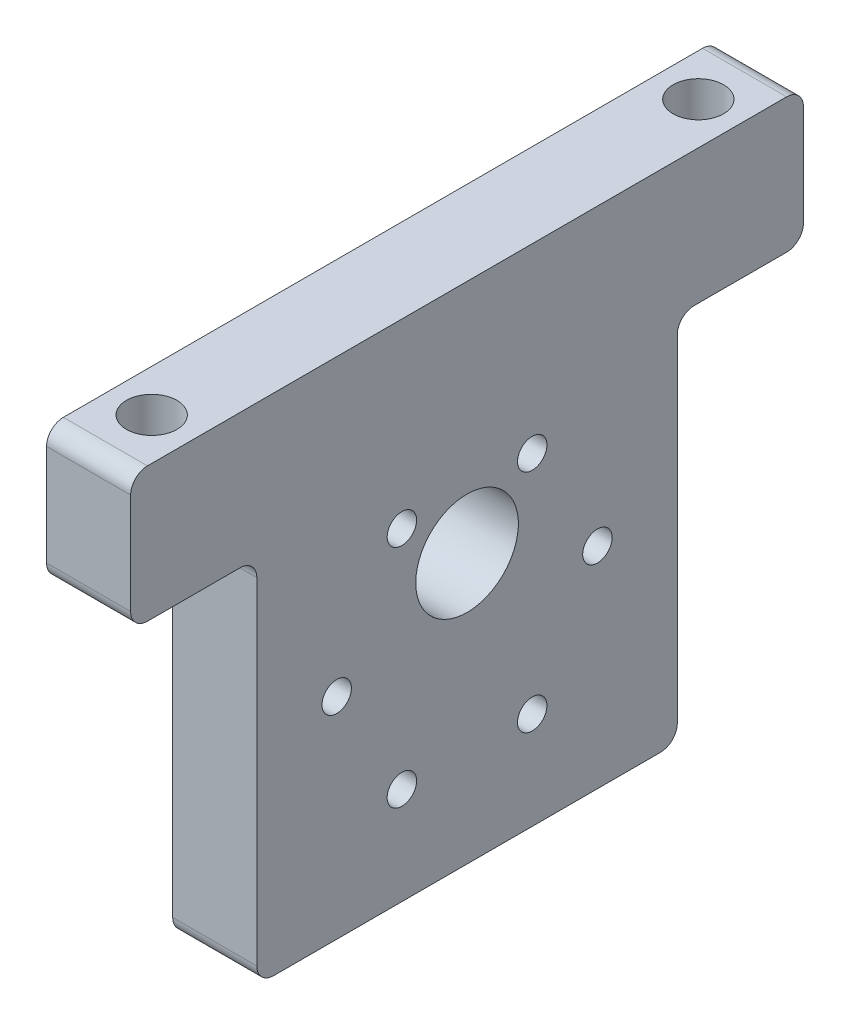
SolidWorks part; units mm, degrees
material "Alloy Steel"
ref_plane "Front Plane" through (0, 0, 0) normal (0, 0, 1) x (1, 0, 0)
ref_plane "Top Plane" through (0, 0, 0) normal (0, 1, 0) x (1, 0, 0)
ref_plane "Right Plane" through (0, 0, 0) normal (1, 0, 0) x (0, 0, -1)
sketch "Sketch1" plane through (0, 0, 0) normal (1, 0, 0) x (0, 0, -1)
  line L1 (-40, 35) -> (40, 35)
  line L2 (-40, 35) -> (-40, -25)
  line L3 (-40, -25) -> (40, -25)
  line L4 (40, 35) -> (40, -25)
  dimension "D1" = 80
  dimension "D2" = 60
  dimension "D3" = 25
  dimension "D4" = 40
extrude "Boss-Extrude1" add sketch "Sketch1" along normal blind 10
sketch "Sketch2" plane through (10, 0, 0) normal (1, 0, 0) x (0, 0, -1)
  line L0 (-15.3693, 0) -> (21.9111, 0) construction
  circle A0 centre (0, -7) radius 6.1 construction
  circle A1 centre (0, 7) radius 6.1
  dimension "D1" = 7
  dimension "D2" = 12.2
extrude "Cut-Extrude1" cut sketch "Sketch2" against normal through all
sketch "Sketch3" plane through (10, 0, 0) normal (1, 0, 0) x (0, 0, -1)
  line L0 (0, 17.2761) -> (0, -21.6696) construction
  line L1 (14.0763, 0) -> (-14.2715, 0) construction
  circle A2 centre (0, 0) radius 15.5 construction
  circle A3 centre (7.75, -13.4234) radius 1.75
  circle A4 centre (-7.75, -13.4234) radius 1.75
  circle A5 centre (-7.75, 13.4234) radius 1.75
  circle A6 centre (7.75, 13.4234) radius 1.75
  circle A7 centre (15.5, 0) radius 1.75
  circle A8 centre (-15.5, 0) radius 1.75
  circle A9 centre (0, 7) radius 6.1 construction
  point P16 (0, 0)
  dimension "D1" = 7
  dimension "D4" = 31
  dimension "D2" = 3.5
  dimension "D5" = 3.5
  dimension "D3" = 7.75
extrude "Cut-Extrude3" cut sketch "Sketch3" against normal through all
sketch "Sketch4" plane through (10, 0, 0) normal (1, 0, 0) x (0, 0, -1)
  line L0 (-40, 35) -> (-40, -25) construction
  line L1 (-40, -25) -> (-25, -25)
  line L2 (-40, -25) -> (-40, 19)
  line L3 (-40, 19) -> (-25, 19)
  line L4 (-25, -25) -> (-25, 19)
  line L5 (0, 35) -> (0, 29.7163) construction
  line L6 (40, 35) -> (-40, 35) construction
  line L7 (25, -25) -> (25, 19)
  line L8 (40, 19) -> (25, 19)
  line L9 (40, -25) -> (40, 19)
  line L10 (40, -25) -> (25, -25)
  dimension "D1" = 15
  dimension "D2" = 44
extrude "Cut-Extrude4" cut sketch "Sketch4" against normal blind 50
sketch "Sketch5" plane through (0, 35, 0) normal (0, 1, 0) x (1, 0, 0)
  line L0 (5, 40) -> (5, 32.5) construction
  line L1 (10, 40) -> (0, 40) construction
  line L2 (0, 0) -> (10, 0) construction
  line L3 (10, 40) -> (10, -40) construction
  circle A0 centre (5, 32.5) radius 3
  circle A1 centre (5, -32.5) radius 3
  dimension "D1" = 7.5
  dimension "D2" = 6
extrude "Cut-Extrude5" cut sketch "Sketch5" against normal blind 50
fillet "Fillet1" radius 2 8 edges at (5, 19, 25) (5, 19, 40) (5, 35, 40) (5, 35, -40) (5, 19, -25) (5, 19, -40) (5, -25, 25) (5, -25, -25)
equation "\"D4@Sketch1\"=\"D1@Sketch1\"/2"
